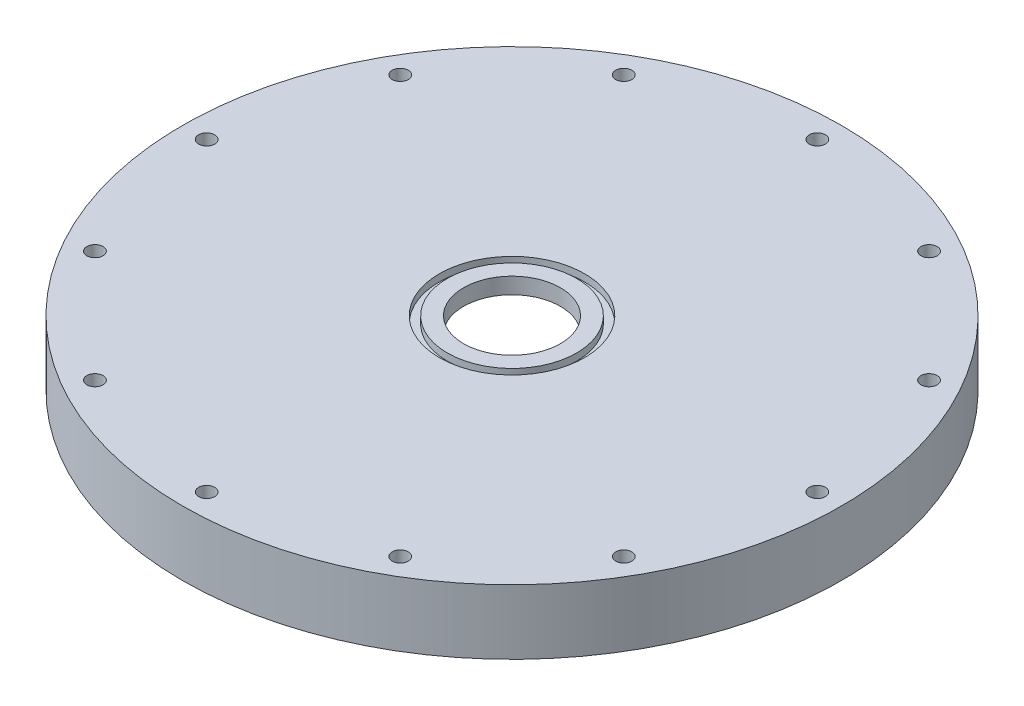
SolidWorks part; units mm, degrees
ref_plane "Front Plane" through (0, 0, 0) normal (0, 0, 1) x (1, 0, 0)
ref_plane "Top Plane" through (0, 0, 0) normal (0, 1, 0) x (1, 0, 0)
ref_plane "Right Plane" through (0, 0, 0) normal (1, 0, 0) x (0, 0, -1)
sketch "Sketch1" plane through (0, 0, 0) normal (0, 0, 1) x (1, 0, 0)
  line L0 (0, 0) -> (0, 6.35)
  line L1 (0, 6.35) -> (-129.54, 6.35)
  line L2 (-129.54, 6.35) -> (-129.54, -19.05)
  line L3 (-129.54, -19.05) -> (-86.36, -19.05)
  line L4 (-86.36, -19.05) -> (-86.36, -16.51)
  line L5 (-69.85, 0) -> (0, 0)
  arc A0 (-86.36, -16.51) -> (-69.85, 0) centre (-69.85, -16.51) cw
  dimension "D5" = 16.51
  dimension "D1" = 129.54
  dimension "D2" = 6.35
  dimension "D3" = 25.4
  dimension "D4" = 43.18
revolve "Revolve1" add sketch "Sketch1" angle 360 about L0
sketch "Sketch2" plane through (0, 6.35, 0) normal (0, 1, 0) x (1, 0, 0)
  circle A0 centre (0, 0) radius 19.05
extrude "Cut-Extrude1" cut sketch "Sketch2" against normal through all
sketch "Sketch3" plane through (0, 6.35, 0) normal (0, 1, 0) x (1, 0, 0)
  circle A0 centre (0, 0) radius 25.4
  circle A1 centre (0, 0) radius 28.575
  dimension "D1" = 57.15
  dimension "D2" = 50.8
extrude "Cut-Extrude2" cut sketch "Sketch3" against normal blind 2.794
sketch "Sketch4" plane through (0, 6.35, 0) normal (0, 1, 0) x (1, 0, 0)
  point P0 (0, 120.015)
  point P5 (60.0075, 103.936)
  point P6 (103.936, 60.0075)
  point P7 (120.015, 0)
  point P8 (103.936, -60.0075)
  point P9 (60.0075, -103.936)
  point P10 (0, -120.015)
  point P11 (-60.0075, -103.936)
  point P12 (-103.936, -60.0075)
  point P13 (-120.015, 0)
  point P14 (-103.936, 60.0075)
  point P15 (-60.0075, 103.936)
  point P16 (0, 0)
  dimension "D1" = 120.015
  dimension "D2" = 12
hole_wizard "1/4 (0.25) Diameter Hole1" positions "3DSketch1" profile "Sketch5" hole size "1/4" standard "ANSI Inch" end condition through all
sketch3d "3DSketch1"
  point P0 (0, 6.35, -120.015)
  point P3 (-60.0075, 6.35, -103.936)
  point P6 (-103.936, 6.35, -60.0075)
  point P9 (-120.015, 6.35, 0)
  point P12 (-103.936, 6.35, 60.0075)
  point P15 (-60.0075, 6.35, 103.936)
  point P18 (0, 6.35, 120.015)
  point P21 (60.0075, 6.35, 103.936)
  point P24 (103.936, 6.35, 60.0075)
  point P27 (120.015, 6.35, 0)
  point P30 (103.936, 6.35, -60.0075)
  point P33 (60.0075, 6.35, -103.936)
sketch "Sketch5" plane through (0, 6.35, -120.015) normal (1, 0, 0) x (0, 0, 1)
  line L0 (0, 0) -> (0, 25.4)
  line L1 (0, 25.4) -> (3.175, 25.4)
  line L2 (3.175, 25.4) -> (3.175, 0)
  line L5 (3.175, 0) -> (0, 0)
  line L11 (0, -6.35) -> (0, 107.95) construction
  dimension "Thru Hole Dia." = 6.35
  dimension "Thru Hole Depth" = 25.4
